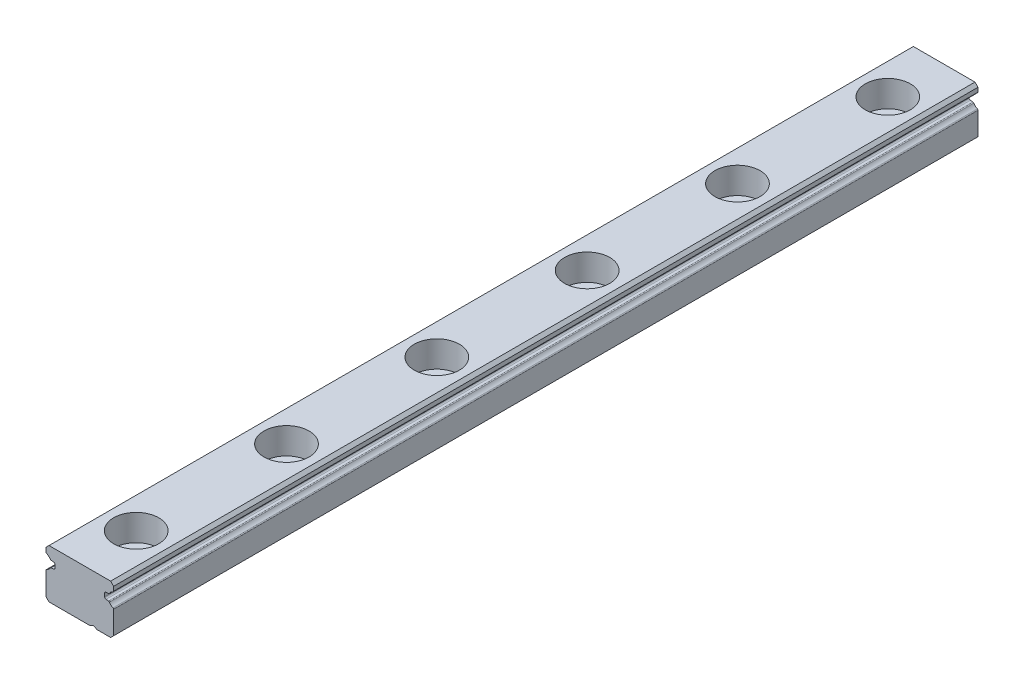
SolidWorks part; units mm, degrees
ref_plane "Front Plane" through (0, 0, 0) normal (0, 0, 1) x (1, 0, 0)
ref_plane "Top Plane" through (0, 0, 0) normal (0, 1, 0) x (1, 0, 0)
ref_plane "Right Plane" through (0, 0, 0) normal (1, 0, 0) x (0, 0, -1)
sketch "Sketch1" plane through (0, 0, 0) normal (0, 0, 1) x (1, 0, 0)
  line L0 (-4.5, 0) -> (4.5, 0) construction
  line L1 (0, -3.25) -> (0, 3.25) construction
  line L2 (0, 3.25) -> (0, -3.25) construction
  line L3 (-3, 3.25) -> (3, 3.25) construction
  line L4 (-1.75, -0.25) -> (1.75, -0.25) construction
  point P0 (0, -0.25)
  point P3 (-4.5, -3.25)
  point P4 (0, 0)
  point P8 (0, 0)
  point P11 (0, 3.25)
  point P15 (0, 3.25)
  point P17 (0, -0.25)
  point P18 (4.5, 3.25)
  point P20 (-4.5, 3.25)
  dimension "Rail Width" = 9
  dimension "Rail Height" = 6.5
  dimension "Mounting Hole Depth" = 3
  dimension "Mounting Hole Counterbore Diameter" = 6
  dimension "Mounting Hole Diameter" = 3.5
sketch "Sketch2" plane through (0, 0, 0) normal (1, 0, 0) x (0, 0, -1)
  line L0 (57.5, 0) -> (-57.5, 0) construction
  line L1 (-3, 3.25) -> (3, 3.25) construction
  line L3 (0, 3.25) -> (0, 0) construction
  point P0 (-50, 0)
  point P4 (0, 0)
  point P5 (-30, 0)
  point P6 (-40, 0)
  point P9 (-50, 3.25)
  point P10 (0, 3.25)
  point P11 (57.5, 3.25)
  point P13 (-57.5, 3.25)
  point P14 (40, 0)
  point P17 (-57.5, -3.25)
  dimension "Rail Length" = 115
  dimension "Mounting Hole Center to Edge" = 7.5
  dimension "Mounting Hole Center to Center" = 20
  dimension "Number of Mounting Holes" = 6
  dimension "Break Line" = 10
sketch "Sketch3" plane through (0, 0, 0) normal (0, 0, 1) x (1, 0, 0)
  point P0 (0, 3.25)
  line B0 (-4.5, 0.1917) -> (-4.5, -2.85)
  line B1 (-4.5, -2.85) -> (-4.1, -3.25)
  line B2 (-4.1, -3.25) -> (1.4, -3.25)
  line B3 (2.2, -3.25) -> (4.1, -3.25)
  line B4 (4.1, -3.25) -> (4.5, -2.85)
  line B5 (4.5, -2.85) -> (4.5, 0.1917)
  line B6 (3.8235, 0.8135) -> (3.4826, 0.8434)
  line B7 (3.3, 1.0426) -> (3.3, 1.4574)
  line B8 (3.4826, 1.6566) -> (3.8235, 1.6865)
  line B9 (4.5, 2.3083) -> (4.5, 2.85)
  line B10 (4.5, 2.85) -> (4.1, 3.25)
  line B11 (4.1, 3.25) -> (-4.1, 3.25)
  line B12 (-4.1, 3.25) -> (-4.5, 2.85)
  line B13 (-4.5, 2.85) -> (-4.5, 2.3083)
  line B14 (-3.8235, 1.6865) -> (-3.4826, 1.6566)
  line B15 (-3.3, 1.4574) -> (-3.3, 1.0426)
  line B16 (-3.4826, 0.8434) -> (-3.8235, 0.8135)
  arc B17 (2.2, -3.25) -> (1.4, -3.25) centre (1.8, -3.55) ccw
  arc B18 (4.5, 0.1917) -> (4.4087, 0.3297) centre (4.35, 0.1917) ccw
  arc B19 (3.9395, 0.7405) -> (4.4087, 0.3297) centre (4.8, 1.25) ccw
  arc B20 (3.9395, 0.7405) -> (3.8235, 0.8135) centre (3.8104, 0.6641) ccw
  arc B21 (3.3, 1.0426) -> (3.4826, 0.8434) centre (3.5, 1.0426) ccw
  arc B22 (3.4826, 1.6566) -> (3.3, 1.4574) centre (3.5, 1.4574) ccw
  arc B23 (3.8235, 1.6865) -> (3.9395, 1.7595) centre (3.8104, 1.8359) ccw
  arc B24 (4.4087, 2.1703) -> (3.9395, 1.7595) centre (4.8, 1.25) ccw
  arc B25 (4.4087, 2.1703) -> (4.5, 2.3083) centre (4.35, 2.3083) ccw
  arc B26 (-4.5, 2.3083) -> (-4.4087, 2.1703) centre (-4.35, 2.3083) ccw
  arc B27 (-3.9395, 1.7595) -> (-4.4087, 2.1703) centre (-4.8, 1.25) ccw
  arc B28 (-3.9395, 1.7595) -> (-3.8235, 1.6865) centre (-3.8104, 1.8359) ccw
  arc B29 (-3.3, 1.4574) -> (-3.4826, 1.6566) centre (-3.5, 1.4574) ccw
  arc B30 (-3.4826, 0.8434) -> (-3.3, 1.0426) centre (-3.5, 1.0426) ccw
  arc B31 (-3.8235, 0.8135) -> (-3.9395, 0.7405) centre (-3.8104, 0.6641) ccw
  arc B32 (-4.4087, 0.3297) -> (-3.9395, 0.7405) centre (-4.8, 1.25) ccw
  arc B33 (-4.4087, 0.3297) -> (-4.5, 0.1917) centre (-4.35, 0.1917) ccw
sketch_block_instance "9mm Block-1"
sketch_block "9mm Block"
extrude "Boss-Extrude1" add sketch "Sketch3" against normal up to vertex (57.5 mm away) from vertex at 57.5 starting at point (0, 0, 57.5)
ref_plane "Plane1" through (0, 0, 50) normal (0, 0, 1) x (1, 0, 0)
sketch "Sketch4" plane through (0, 0, 50) normal (0, 0, 1) x (1, 0, 0)
  line L0 (0, 3.25) -> (0, -3.25)
  line L1 (0, -3.25) -> (-1.75, -3.25)
  line L3 (-1.75, -3.25) -> (-1.75, -0.25)
  line L4 (-1.75, -0.25) -> (-3, -0.25)
  line L5 (-3, -0.25) -> (-3, 3.25)
  line L6 (-3, 3.25) -> (0, 3.25)
revolve "Cut-Revolve1" cut sketch "Sketch4" angle 360 about L0
sketch "Sketch6" plane through (0, 0, 0) normal (1, 0, 0) x (0, 0, -1)
  line L0 (-47, -0.25) -> (-53, -0.25) construction
  line L5 (-47, -0.25) -> (-53, -0.25)
  line L17 (-51.75, -0.25) -> (-51.75, -3.25) construction
  line L18 (-48.25, -3.25) -> (-48.25, -0.25) construction
  line L32 (-47, -0.25) -> (-47, 3.25) construction
  line L33 (-53, 3.25) -> (-53, -0.25) construction
  line L34 (-51.75, -0.25) -> (-51.75, -3.25)
  line L35 (-48.25, -3.25) -> (-48.25, -0.25)
  line L36 (-47, -0.25) -> (-47, 3.25)
  line L37 (-53, 3.25) -> (-53, -0.25)
  line L38 (0, 3.25) -> (0, -3.25) construction
  line L40 (53, 3.25) -> (53, -0.25)
  line L41 (47, -0.25) -> (47, 3.25)
  line L42 (48.25, -3.25) -> (48.25, -0.25)
  line L43 (51.75, -0.25) -> (51.75, -3.25)
  line L44 (47, -0.25) -> (53, -0.25)
sketch "Sketch7" plane through (0, 0, 0) normal (0, 0, 1) x (1, 0, 0)
  line L0 (3, -0.25) -> (3, 3.25) construction
  line L1 (-3, 3.25) -> (-3, -0.25) construction
  line L2 (3, -0.25) -> (3, 3.25)
  line L3 (-3, 3.25) -> (-3, -0.25)
  line L4 (1.75, -3.0525) -> (1.75, -0.25) construction
  line L11 (1.75, -3.0525) -> (1.75, -0.25)
  line L18 (-1.75, -0.25) -> (-1.75, -3.25) construction
  line L32 (3, -0.25) -> (-3, -0.25) construction
  line L34 (-1.75, -0.25) -> (-1.75, -3.25)
  line L37 (3, -0.25) -> (-3, -0.25)
pattern_linear "LPattern1" count 6 spacing 20 along (0, 0, -1) of "Cut-Revolve1"
equation "\"D3@LPattern1\"=\"Mounting Hole Center to Center@Sketch2\""
equation "\"D1@LPattern1\"=\"Number of Mounting Holes@Sketch2\""
equation "\"Break Line@Sketch2\"=\"Mounting Hole Center to Center@Sketch2\"/2"
